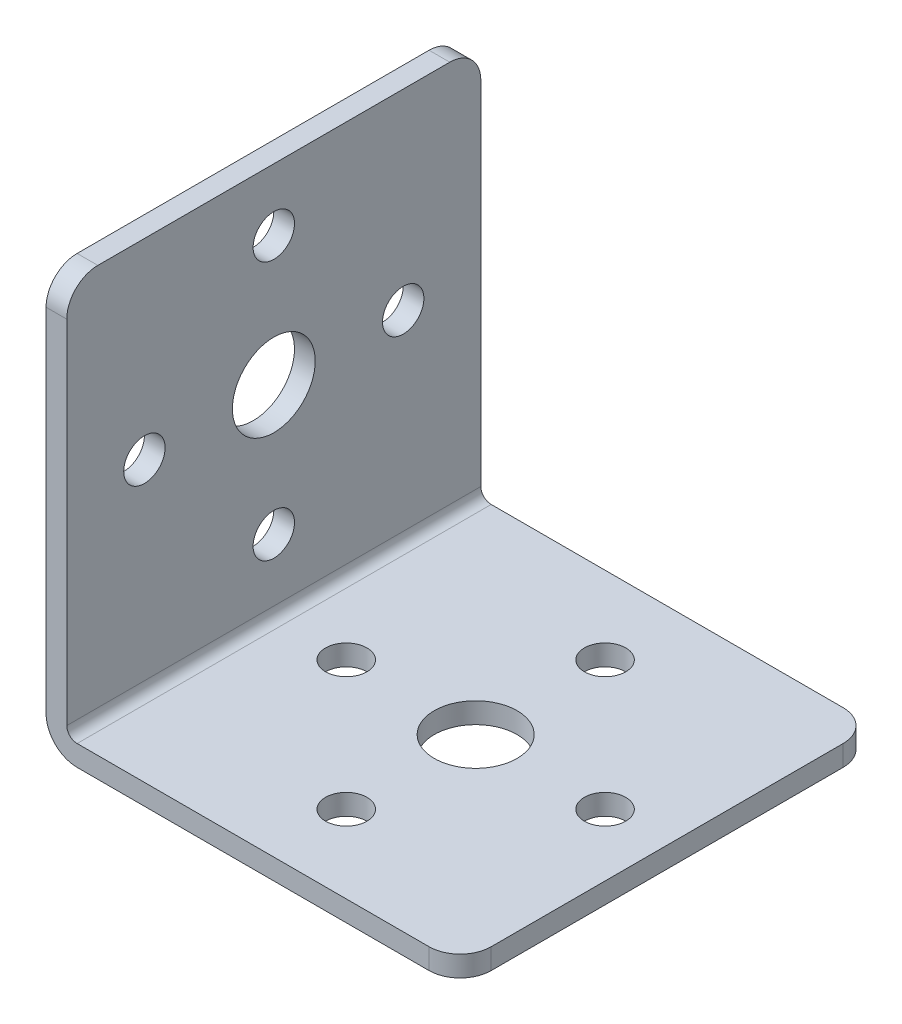
SolidWorks part; units mm, degrees
material "AISI 316 Отожженная нержавеющая сталь. полоса (SS)"
ref_plane "Спереди XY" through (0, 0, 0) normal (0, 0, 1) x (1, 0, 0)
ref_plane "Сверху XZ" through (0, 0, 0) normal (0, 1, 0) x (1, 0, 0)
ref_plane "Справа ZY" through (0, 0, 0) normal (1, 0, 0) x (0, 0, -1)
sketch "Эскиз1" plane through (0, 0, 0) normal (0, 0, 1) x (1, 0, 0)
  line L0 (-3, 37) -> (-3, 0)
  line L1 (0, -3) -> (37, -3)
  line L2 (-1, 37) -> (-1, 0)
  line L3 (0, -1) -> (37, -1)
  line L4 (-3, 37) -> (-1, 37)
  line L5 (37, -1) -> (37, -3)
  arc A0 (-3, 0) -> (0, -3) centre (0, 0) ccw
  arc A1 (-1, 0) -> (0, -1) centre (0, 0) ccw
  dimension "D4" = 1
  dimension "D1" = 40
  dimension "D2" = 40
  dimension "D3" = 2
extrude "Бобышка-Вытянуть1" add sketch "Эскиз1" along normal blind 40
sketch "Эскиз2" plane through (-3, 0, 0) normal (-1, 0, 0) x (0, 0, 1)
  line L0 (20, 37) -> (20, -9.5944) construction
  line L1 (40, 37) -> (0, 37) construction
  line L2 (0, 18.5) -> (20, 18.5) construction
  line L3 (0, 37) -> (0, 0) construction
  circle A0 centre (7.5, 18.5) radius 2
  circle A1 centre (20, 31) radius 2
  circle A2 centre (20, 18.5) radius 4
  circle A3 centre (32.5, 18.5) radius 2
  circle A4 centre (20, 6) radius 2
  point P19 (20, 18.5)
  point P21 (20, 18.5)
  dimension "D1" = 4
  dimension "D3" = 8
  dimension "D2" = 12.5
  dimension "D4" = 4
extrude "Вырез-Вытянуть1" cut sketch "Эскиз2" against normal blind 40
sketch "Эскиз3" plane through (0, -3, 0) normal (0, -1, 0) x (1, 0, 0)
  line L0 (0, 20) -> (37, 20) construction
  line L1 (0, 40) -> (0, 0) construction
  line L2 (37, 40) -> (37, 0) construction
  line L3 (18.5, 20) -> (18.5, 0) construction
  line L4 (0, 0) -> (37, 0) construction
  circle A0 centre (18.5, 7.5) radius 2
  circle A1 centre (6, 20) radius 2
  circle A2 centre (18.5, 32.5) radius 2
  circle A3 centre (31, 20) radius 2
  circle A4 centre (18.5, 20) radius 4
  point P21 (18.5, 20)
  dimension "D1" = 4
  dimension "D4" = 8
  dimension "D2" = 12.5
  dimension "D3" = 4
extrude "Вырез-Вытянуть2" cut sketch "Эскиз3" against normal blind 40
fillet "Скругление1" radius 3 4 edges at (37, -2, 0) (37, -2, 40) (-2, 37, 40) (-2, 37, 0)
